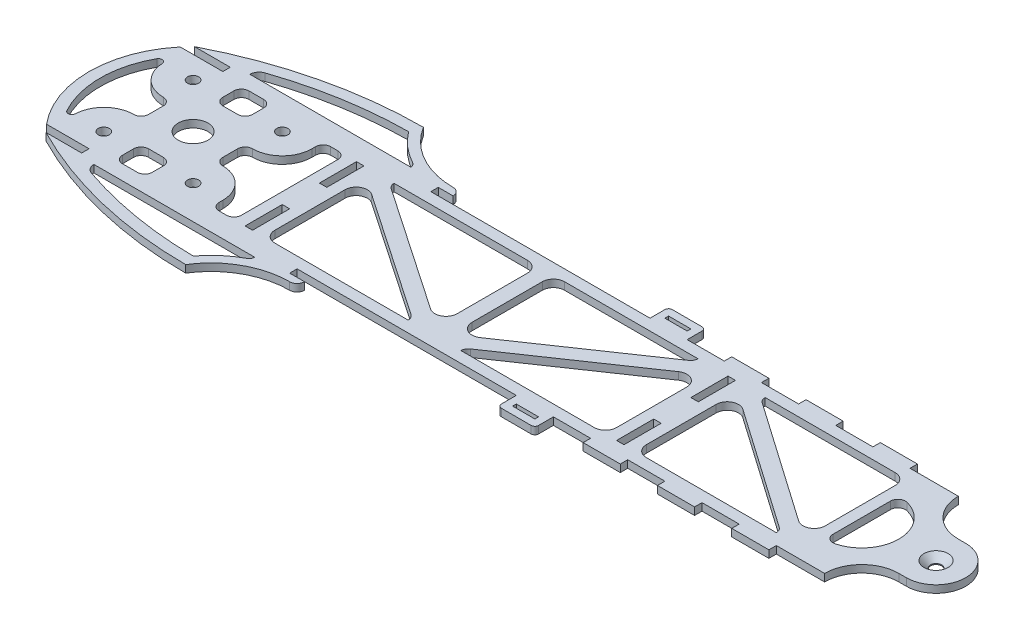
SolidWorks part; units mm, degrees
ref_plane "Front Plane" through (0, 0, 0) normal (0, 0, 1) x (1, 0, 0)
ref_plane "Top Plane" through (0, 0, 0) normal (0, 1, 0) x (1, 0, 0)
ref_plane "Right Plane" through (0, 0, 0) normal (1, 0, 0) x (0, 0, -1)
sketch "Sketch1" plane through (0, 0, 0) normal (0, 1, 0) x (1, 0, 0)
  line L0 (-19.5959, 20) -> (-10, 20)
  line L1 (-40, 0) -> (219.75, 0) construction
  line L2 (-21.4476, 18) -> (-10, 18)
  line L3 (20, 12) -> (20, 13)
  line L4 (22, 15) -> (24, 15)
  line L5 (26, 13) -> (26, -13)
  line L6 (50, 20) -> (46, 20)
  line L7 (10, 2) -> (10, -2)
  line L8 (46, 20) -> (46, 18)
  line L9 (-10, 2) -> (-10, -2)
  line L10 (-4, 15) -> (-4, 12)
  line L11 (4, 15) -> (4, 12)
  line L12 (-2, 10) -> (2, 10)
  line L13 (-2, 17) -> (2, 17)
  line L14 (46, 18) -> (105, 18)
  line L15 (-10, 18) -> (-10, 20)
  line L16 (-5.706, 21) -> (37.5752, 21)
  line L17 (105, 18) -> (105, 22)
  line L18 (29, 15) -> (31, 15)
  line L19 (29, 15) -> (29, 5)
  line L20 (29, 5) -> (31, 5)
  line L21 (31, 15) -> (31, 5)
  line L22 (106, 23) -> (114, 23)
  line L23 (115, 22) -> (115, 18)
  line L24 (115, 18) -> (125, 18)
  line L25 (135, 18) -> (145, 18)
  line L26 (107, 21) -> (113, 21)
  line L27 (107, 21) -> (107, 20)
  line L28 (107, 20) -> (113, 20)
  line L29 (113, 21) -> (113, 20)
  line L30 (155, 18) -> (165, 18)
  line L31 (125, 18) -> (125, 20)
  line L32 (125, 20) -> (135, 20)
  line L33 (135, 18) -> (135, 20)
  line L34 (175, 18) -> (188, 18)
  line L35 (145, 18) -> (145, 20)
  line L36 (145, 20) -> (155, 20)
  line L37 (155, 18) -> (155, 20)
  line L38 (200, 8) -> (198, 8)
  line L39 (165, 18) -> (165, 20)
  line L40 (165, 20) -> (175, 20)
  line L41 (175, 18) -> (175, 20)
  line L42 (180, 7.746) -> (180, -7.746)
  line L43 (175, -18) -> (175, -20)
  line L44 (165, -20) -> (175, -20)
  line L45 (165, -18) -> (165, -20)
  line L46 (200, -8) -> (198, -8)
  line L47 (155, -18) -> (155, -20)
  line L48 (145, -20) -> (155, -20)
  line L49 (145, -18) -> (145, -20)
  line L50 (175, -18) -> (188, -18)
  line L51 (135, -18) -> (135, -20)
  line L52 (125, -20) -> (135, -20)
  line L53 (125, -18) -> (125, -20)
  line L54 (155, -18) -> (165, -18)
  line L55 (113, -21) -> (113, -20)
  line L56 (107, -20) -> (113, -20)
  line L57 (107, -21) -> (107, -20)
  line L58 (107, -21) -> (113, -21)
  line L59 (135, -18) -> (145, -18)
  line L60 (115, -18) -> (125, -18)
  line L61 (115, -22) -> (115, -18)
  line L62 (106, -23) -> (114, -23)
  line L63 (31, -15) -> (31, -5)
  line L64 (29, -5) -> (31, -5)
  line L65 (29, -15) -> (29, -5)
  line L66 (29, -15) -> (31, -15)
  line L67 (105, -18) -> (105, -22)
  line L68 (-5.706, -21) -> (37.5752, -21)
  line L69 (-10, -18) -> (-10, -20)
  line L70 (46, -18) -> (105, -18)
  line L71 (-2, -17) -> (2, -17)
  line L72 (-2, -10) -> (2, -10)
  line L73 (4, -15) -> (4, -12)
  line L74 (-4, -15) -> (-4, -12)
  line L75 (46, -20) -> (46, -18)
  line L76 (50, -20) -> (46, -20)
  line L77 (22, -15) -> (24, -15)
  line L78 (20, -12) -> (20, -13)
  line L79 (-21.4476, -18) -> (-10, -18)
  line L80 (-19.5959, -20) -> (-10, -20)
  line L81 (139.8464, 13.3597) -> (172.2835, -9.2707)
  line L82 (39.1005, 15) -> (75, 15)
  line L83 (34, 6.9029) -> (34, -12)
  line L84 (37, -15) -> (72.8995, -15)
  line L85 (78, 12) -> (78, -6.9029)
  line L86 (0, 0) -> (14.6778, 14.6778) construction
  line L87 (38.69, 9.3816) -> (72.0261, -13.3475)
  line L88 (85, 15) -> (120.8995, 15)
  line L89 (39.9739, 13.3475) -> (73.31, -9.3816)
  line L90 (82, 12) -> (82, -6.9029)
  line L91 (138.9908, 15) -> (174, 15)
  line L92 (126, 6.9029) -> (126, -12)
  line L94 (129, 15) -> (131, 15)
  line L95 (129, 15) -> (129, 5)
  line L96 (129, 5) -> (131, 5)
  line L97 (131, 15) -> (131, 5)
  line L98 (129, -5) -> (131, -5)
  line L99 (129, -5) -> (129, -15)
  line L100 (129, -15) -> (131, -15)
  line L101 (131, -5) -> (131, -15)
  line L103 (134, 6.8104) -> (134, -12)
  line L104 (137, -15) -> (172.0092, -15)
  line L105 (177, 12) -> (177, -6.8104)
  line L107 (138.7165, 9.2707) -> (171.1536, -13.3597)
  line L108 (86.69, -9.3816) -> (120.0261, 13.3475)
  line L110 (87.9739, -13.3475) -> (121.31, 9.3816)
  line L114 (87.1005, -15) -> (123, -15)
  circle A0 centre (0, 0) radius 4
  arc A1 (-21.4476, 18) -> (-21.4476, -18) centre (0, 0) ccw
  circle A2 centre (12.0208, 12.0208) radius 1.5
  arc A3 (-21.8672, 12.1172) -> (-21.8672, -12.1172) centre (0, 0) ccw
  arc A4 (30, 32) -> (-19.5959, 20) centre (30, -76.4898) ccw
  arc A5 (-19.9933, 11.6733) -> (-12, 4) centre (-12, 12) ccw
  circle A6 centre (12.0208, -12.0208) radius 1.5
  arc A7 (12, 4) -> (20, 12) centre (12, 12) ccw
  arc A8 (-19.9933, 11.6733) -> (-21.8672, 12.1172) centre (-20.9925, 11.6325) ccw
  arc A9 (-2, 17) -> (-4, 15) centre (-2, 15) ccw
  arc A10 (2, 17) -> (4, 15) centre (2, 15) cw
  arc A11 (2, 10) -> (4, 12) centre (2, 12) ccw
  arc A12 (-2, 10) -> (-4, 12) centre (-2, 12) cw
  arc A13 (29.0284, 28.9955) -> (-4.012, 23.3665) centre (30, -76.4898) ccw
  arc A14 (24, 15) -> (26, 13) centre (24, 13) cw
  arc A15 (30, 29) -> (-18.2245, 17.3318) centre (30, -76.4898) ccw construction
  arc A16 (20, 13) -> (22, 15) centre (22, 13) cw
  arc A17 (-10, 2) -> (-12, 4) centre (-12, 2) ccw
  arc A18 (12, 4) -> (10, 2) centre (12, 2) ccw
  arc A19 (50, 20) -> (48, 22) centre (48, 20) ccw
  arc A20 (30, 32) -> (48, 22) centre (48, 43.2) ccw
  arc A21 (29.0284, 28.9955) -> (36.785, 22.3214) centre (48, 43.2) ccw
  arc A22 (37.5752, 21) -> (36.785, 22.3214) centre (36.0752, 21) ccw
  arc A23 (27.8774, 30.6792) -> (48, 19.5) centre (48, 43.2) ccw construction
  arc A24 (-4.012, 23.3665) -> (-5.706, 21) centre (-3.206, 21) ccw
  arc A25 (114, 23) -> (115, 22) centre (114, 22) cw
  arc A26 (105, 22) -> (106, 23) centre (106, 22) cw
  circle A27 centre (200, 0) radius 1.5
  arc A28 (200, -8) -> (200, 8) centre (200, 0) ccw
  arc A29 (188, 18) -> (198, 8) centre (198, 18) ccw
  arc A30 (182.5, -9.6825) -> (182.5, 9.6825) centre (180, 0) ccw
  arc A31 (180, 7.746) -> (182.5, 9.6825) centre (182, 7.746) cw
  arc A32 (180, -7.746) -> (182.5, -9.6825) centre (182, -7.746) ccw
  arc A33 (188, -18) -> (198, -8) centre (198, -18) cw
  arc A34 (105, -22) -> (106, -23) centre (106, -22) ccw
  arc A35 (114, -23) -> (115, -22) centre (114, -22) ccw
  arc A36 (-4.012, -23.3665) -> (-5.706, -21) centre (-3.206, -21) cw
  arc A37 (37.5752, -21) -> (36.785, -22.3214) centre (36.0752, -21) cw
  arc A38 (29.0284, -28.9955) -> (36.785, -22.3214) centre (48, -43.2) cw
  arc A39 (30, -32) -> (48, -22) centre (48, -43.2) cw
  arc A40 (50, -20) -> (48, -22) centre (48, -20) cw
  arc A41 (12, -4) -> (10, -2) centre (12, -2) cw
  arc A42 (-10, -2) -> (-12, -4) centre (-12, -2) cw
  arc A43 (20, -13) -> (22, -15) centre (22, -13) ccw
  arc A44 (24, -15) -> (26, -13) centre (24, -13) ccw
  arc A45 (29.0284, -28.9955) -> (-4.012, -23.3665) centre (30, 76.4898) cw
  arc A46 (-2, -10) -> (-4, -12) centre (-2, -12) ccw
  arc A47 (2, -10) -> (4, -12) centre (2, -12) cw
  arc A48 (2, -17) -> (4, -15) centre (2, -15) ccw
  arc A49 (-2, -17) -> (-4, -15) centre (-2, -15) cw
  arc A50 (-19.9933, -11.6733) -> (-21.8672, -12.1172) centre (-20.9925, -11.6325) cw
  arc A51 (12, -4) -> (20, -12) centre (12, -12) cw
  circle A52 centre (-12.0208, -12.0208) radius 1.5
  arc A53 (-19.9933, -11.6733) -> (-12, -4) centre (-12, -12) cw
  arc A54 (30, -32) -> (-19.5959, -20) centre (30, 76.4898) cw
  circle A55 centre (-12.0208, 12.0208) radius 1.5
  arc A56 (39.1005, 15) -> (39.9739, 13.3475) centre (41.1005, 15) ccw
  arc A57 (72.8995, -15) -> (72.0261, -13.3475) centre (70.8995, -15) ccw
  arc A58 (34, 6.9029) -> (38.69, 9.3816) centre (37, 6.9029) cw
  arc A59 (34, -12) -> (37, -15) centre (37, -12) ccw
  arc A60 (78, -6.9029) -> (73.31, -9.3816) centre (75, -6.9029) cw
  arc A61 (75, 15) -> (78, 12) centre (75, 12) cw
  arc A62 (120.0261, 13.3475) -> (120.8995, 15) centre (118.8995, 15) ccw
  arc A63 (87.9739, -13.3475) -> (87.1005, -15) centre (89.1005, -15) ccw
  arc A64 (172.0092, -15) -> (171.1536, -13.3597) centre (170.0092, -15) ccw
  arc A65 (138.9908, 15) -> (139.8464, 13.3597) centre (140.9908, 15) ccw
  arc A66 (177, -6.8104) -> (172.2835, -9.2707) centre (174, -6.8104) cw
  arc A67 (174, 15) -> (177, 12) centre (174, 12) cw
  arc A68 (134, 6.8104) -> (138.7165, 9.2707) centre (137, 6.8104) cw
  arc A69 (134, -12) -> (137, -15) centre (137, -12) ccw
  arc A70 (123, -15) -> (126, -12) centre (123, -12) ccw
  arc A71 (126, 6.9029) -> (121.31, 9.3816) centre (123, 6.9029) ccw
  arc A72 (85, 15) -> (82, 12) centre (85, 12) ccw
  arc A73 (82, -6.9029) -> (86.69, -9.3816) centre (85, -6.9029) ccw
  point P28 (180, -10)
  point P31 (26, 0)
  point P82 (115, 23)
  point P85 (105, 23)
  point P109 (180, 10)
  point P193 (-10, 0)
  point P194 (10, 0)
  point P195 (105, -23)
  point P196 (115, -23)
  point P197 (34, 15)
  point P198 (78, -15)
  point P201 (32.8733, 13.3475)
  point P203 (76.8733, -16.6525)
  point P204 (35.1267, 16.6525)
  point P205 (79.1267, -13.3475)
  point P224 (82, -15)
  point P225 (126, 15)
  point P234 (134, 15)
  point P235 (177, -15)
  point P238 (83.1267, -16.6525)
  point P239 (127.1267, 13.3475)
  point P240 (132.8556, 13.3597)
  point P241 (175.8556, -16.6403)
  point P242 (80.8733, -13.3475)
  point P243 (124.8733, 16.6525)
  point P244 (135.1444, 16.6403)
  point P245 (178.1444, -13.3597)
  point P285 (0, 0)
  dimension "D1" = 16
  dimension "D2" = 2
  dimension "D3" = 2
  dimension "D5" = 2
  dimension "D6" = 4
  dimension "D7" = 4
  dimension "D9" = 3
  dimension "D10" = 5
  dimension "D14" = 1
  dimension "D15" = 2
  dimension "D18" = 4
  dimension "D17" = 4
  dimension "D16" = 3
  dimension "D21" = 4
  dimension "D22" = 4
  dimension "D23" = 4
  dimension "D24" = 4
  dimension "D19" = 3
  dimension "D20" = 3
  dimension "D25" = 3
  dimension "D11" = 5
  dimension "D12" = 10
  dimension "D13" = 105
  dimension "D26" = 17
  dimension "D4" = 3
  dimension "D8" = 2.5
  dimension "D27" = 4
extrude "Boss-Extrude1" add sketch "Sketch1" along normal blind 2
chamfer "Chamfer1" distance 1.75 angle 45 1 edges at (200, 2, 1.5)
